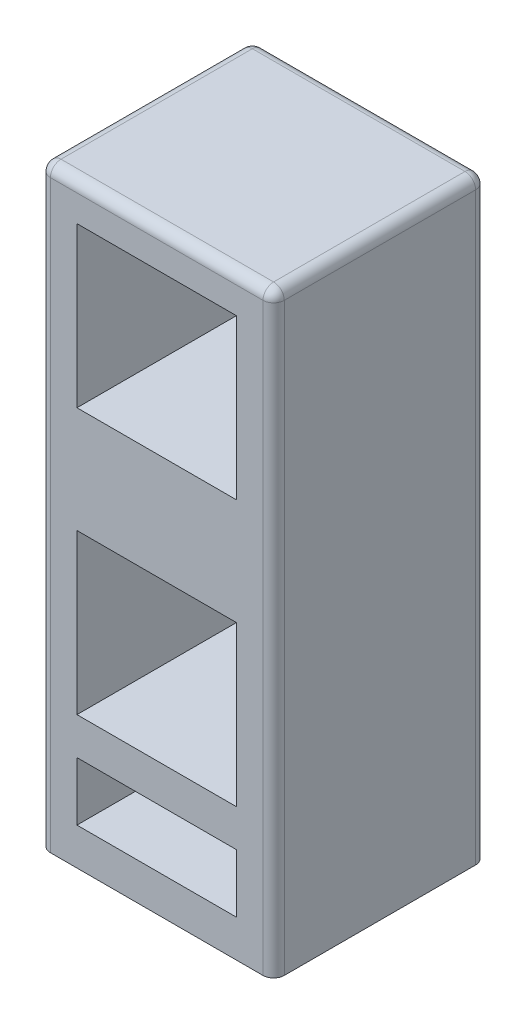
SolidWorks part; units mm, degrees
ref_plane "Front Plane" through (0, 0, 0) normal (0, 0, 1) x (1, 0, 0)
ref_plane "Top Plane" through (0, 0, 0) normal (0, 1, 0) x (1, 0, 0)
ref_plane "Right Plane" through (0, 0, 0) normal (1, 0, 0) x (0, 0, -1)
sketch "Sketch1" plane through (0, 0, 0) normal (0, 0, 1) x (1, 0, 0)
  line L1 (-25.0962, 42.3339) -> (-3.0962, 42.3339)
  line L2 (-25.0962, 42.3339) -> (-25.0962, -13.6661)
  line L3 (-25.0962, -13.6661) -> (-3.0962, -13.6661)
  line L4 (-3.0962, 42.3339) -> (-3.0962, -13.6661)
  line L5 (-21.5962, 38.8339) -> (-6.5962, 38.8339)
  line L6 (-21.5962, 38.8339) -> (-21.5962, 23.8339)
  line L7 (-21.5962, 23.8339) -> (-6.5962, 23.8339)
  line L8 (-6.5962, 38.8339) -> (-6.5962, 23.8339)
  dimension "D1" = 22
  dimension "D2" = 56
  dimension "D3" = 15
  dimension "D4" = 3.5
  dimension "D5" = 3.5
  dimension "D6" = 15
extrude "Boss-Extrude1" add sketch "Sketch1" along normal blind 20
sketch "Sketch2" plane through (0, 0, 20) normal (0, 0, 1) x (1, 0, 0)
  line L0 (-3.0962, -13.6661) -> (-3.0962, 42.3339) construction
  line L1 (-21.5962, 13.8339) -> (-6.5962, 13.8339)
  line L2 (-21.5962, 13.8339) -> (-21.5962, -1.1661)
  line L3 (-21.5962, -1.1661) -> (-6.5962, -1.1661)
  line L4 (-6.5962, 13.8339) -> (-6.5962, -1.1661)
  line L5 (-21.5962, 23.8339) -> (-6.5962, 23.8339) construction
  line L6 (-25.0962, -13.6661) -> (-3.0962, -13.6661) construction
  line L7 (-21.5962, -4.6661) -> (-6.5962, -4.6661)
  line L8 (-21.5962, -4.6661) -> (-21.5962, -10.1661)
  line L9 (-21.5962, -10.1661) -> (-6.5962, -10.1661)
  line L10 (-6.5962, -4.6661) -> (-6.5962, -10.1661)
  dimension "D1" = 15
  dimension "D2" = 3.5
  dimension "D3" = 10
  dimension "D4" = 15
  dimension "D5" = 15
  dimension "D6" = 3.5
  dimension "D7" = 3.5
extrude "Cut-Extrude1" cut sketch "Sketch2" against normal offset from surface (15.5 mm away) 4.5 up to face at (-14.0962, 14.3339, 0)
fillet "Fillet1" radius 1 8 edges at (-14.0962, 42.3339, 0) (-14.0962, 42.3339, 20) (-3.0962, 42.3339, 10) (-3.0962, 14.3339, 0) (-3.0962, 14.3339, 20) (-25.0962, 14.3339, 0) (-25.0962, 14.3339, 20) (-25.0962, 42.3339, 10)
